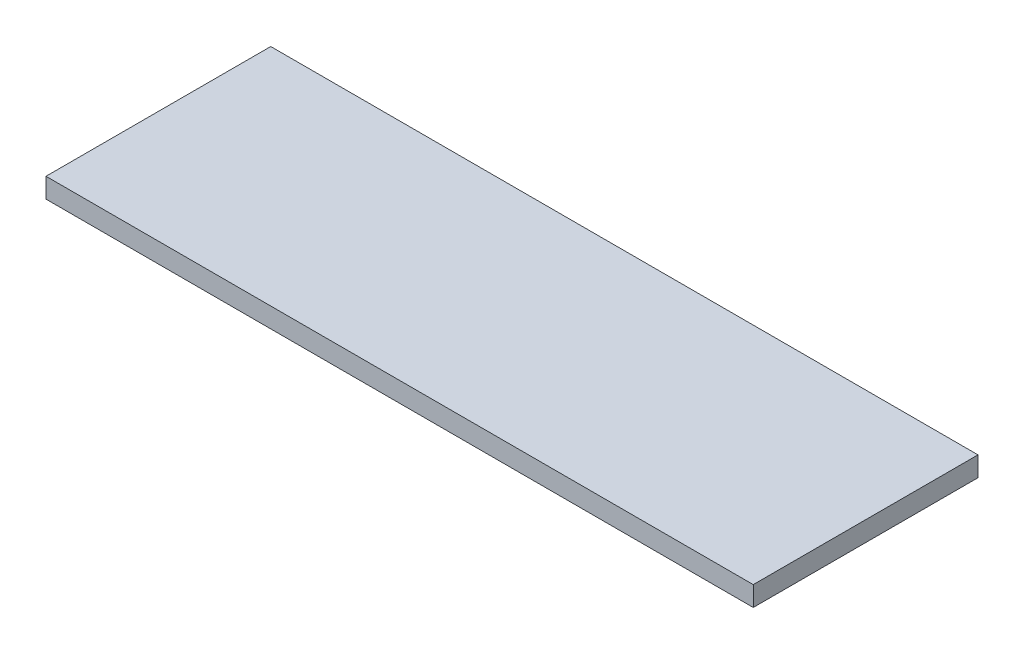
SolidWorks part; units mm, degrees
ref_plane "Front Plane" through (0, 0, 0) normal (0, 0, 1) x (1, 0, 0)
ref_plane "Top Plane" through (0, 0, 0) normal (0, 1, 0) x (1, 0, 0)
ref_plane "Right Plane" through (0, 0, 0) normal (1, 0, 0) x (0, 0, -1)
sketch "Sketch1" plane through (0, 0, 0) normal (0, 1, 0) x (1, 0, 0)
  line L1 (0, 0) -> (107, 0)
  line L2 (0, 0) -> (0, 34)
  line L3 (0, 34) -> (107, 34)
  line L4 (107, 0) -> (107, 34)
  dimension "D1" = 34
  dimension "D2" = 107
extrude "Boss-Extrude1" add sketch "Sketch1" along normal blind 3
